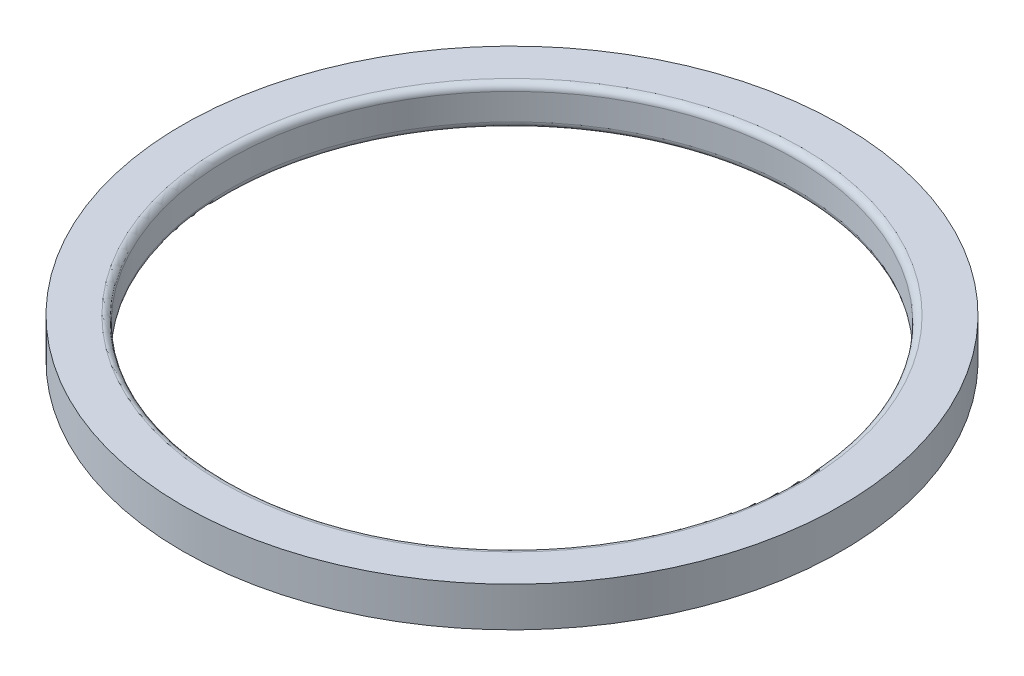
SolidWorks part; units mm, degrees
ref_plane "Front Plane" through (0, 0, 0) normal (0, 0, 1) x (1, 0, 0)
ref_plane "Top Plane" through (0, 0, 0) normal (0, 1, 0) x (1, 0, 0)
ref_plane "Right Plane" through (0, 0, 0) normal (1, 0, 0) x (0, 0, -1)
sketch "Sketch1" plane through (0, 0, 0) normal (0, 1, 0) x (1, 0, 0)
  line L0 (0, 57.7354) -> (0, -54.9267) construction
  circle A0 centre (0, 0) radius 50
  circle A1 centre (0, 0) radius 43
  dimension "D1" = 100
  dimension "D2" = 86
extrude "Boss-Extrude1" add sketch "Sketch1" along normal blind 6
fillet "Fillet1" radius 1 2 edges at (0, 0, 43) (0, 6, 43)
